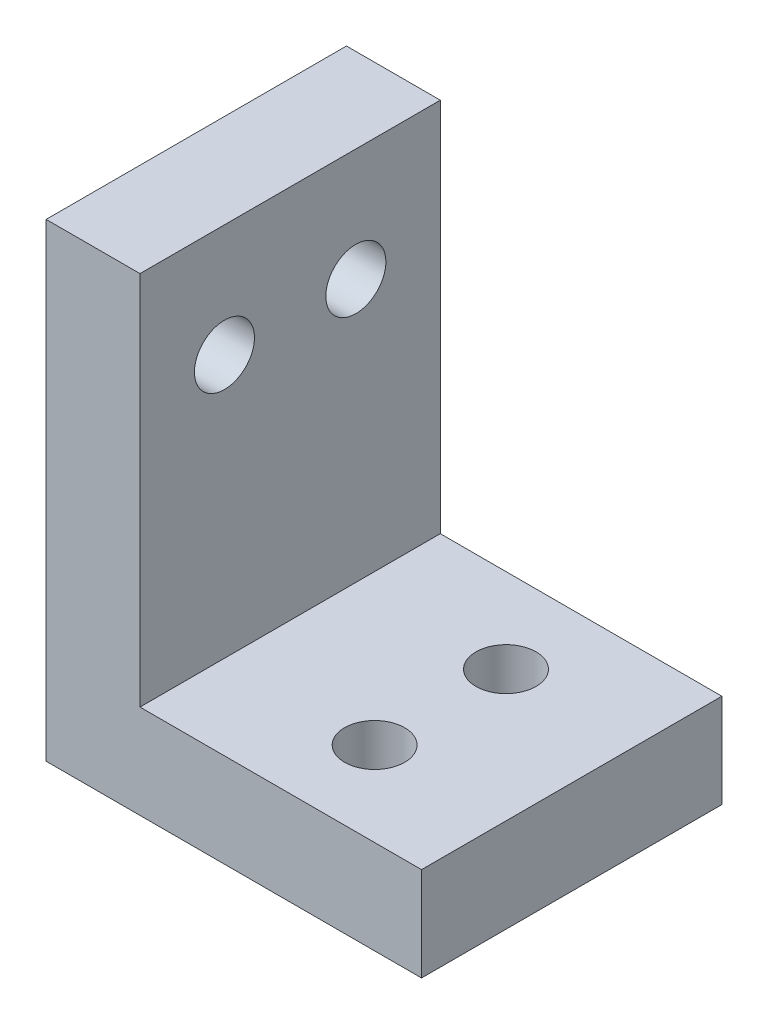
SolidWorks part; units mm, degrees
material "AISI 1015 钢，冷拔 (SS)"
ref_plane "前视基准面" through (0, 0, 0) normal (0, 0, 1) x (1, 0, 0)
ref_plane "上视基准面" through (0, 0, 0) normal (0, 1, 0) x (1, 0, 0)
ref_plane "右视基准面" through (0, 0, 0) normal (1, 0, 0) x (0, 0, -1)
other "Configuration Table"
sketch "草图1" plane through (0, 0, 0) normal (0, 0, 1) x (1, 0, 0)
  line L0 (0, 25) -> (0, 0)
  line L1 (0, 0) -> (20, 0)
  line L2 (20, 0) -> (20, 5)
  line L3 (20, 5) -> (5, 5)
  line L4 (5, 5) -> (5, 25)
  line L5 (5, 25) -> (0, 25)
  dimension "D1" = 5
  dimension "D2" = 5
  dimension "D3" = 20
  dimension "D4" = 25
extrude "凸台-拉伸1" add sketch "草图1" along normal blind 16
sketch "草图4" plane through (0, 5, 0) normal (0, 1, 0) x (1, 0, 0)
  line L0 (20, -16) -> (5, -16) construction
  line L2 (5, -16) -> (5, 0) construction
  line L3 (20, 0) -> (5, 0) construction
  line L5 (5, -16) -> (5, 0) construction
  circle A0 centre (13, -4.5) radius 1.6
  circle A1 centre (13, -11.5) radius 1.6
  dimension "D2" = 3.2
  dimension "D3" = 3.2
  dimension "D1" = 8
  dimension "D4" = 4.5
  dimension "D5" = 4.5
  dimension "D6" = 8
extrude "切除-拉伸3" cut sketch "草图4" against normal blind 38
sketch "草图5" plane through (0, 0, 0) normal (-1, 0, 0) x (0, 0, 1)
  line L1 (16, 25) -> (16, 0) construction
  line L2 (16, 0) -> (0, 0) construction
  line L3 (0, 25) -> (0, 0) construction
  line L4 (16, 25) -> (0, 25) construction
  circle A0 centre (4.5, 19) radius 1.6
  circle A1 centre (11.5, 19) radius 1.6
  dimension "D1" = 3.2
  dimension "D3" = 3.2
  dimension "D2" = 19
  dimension "D4" = 4.5
  dimension "D5" = 4.5
  dimension "D6" = 6
extrude "切除-拉伸4" cut sketch "草图5" against normal blind 38
